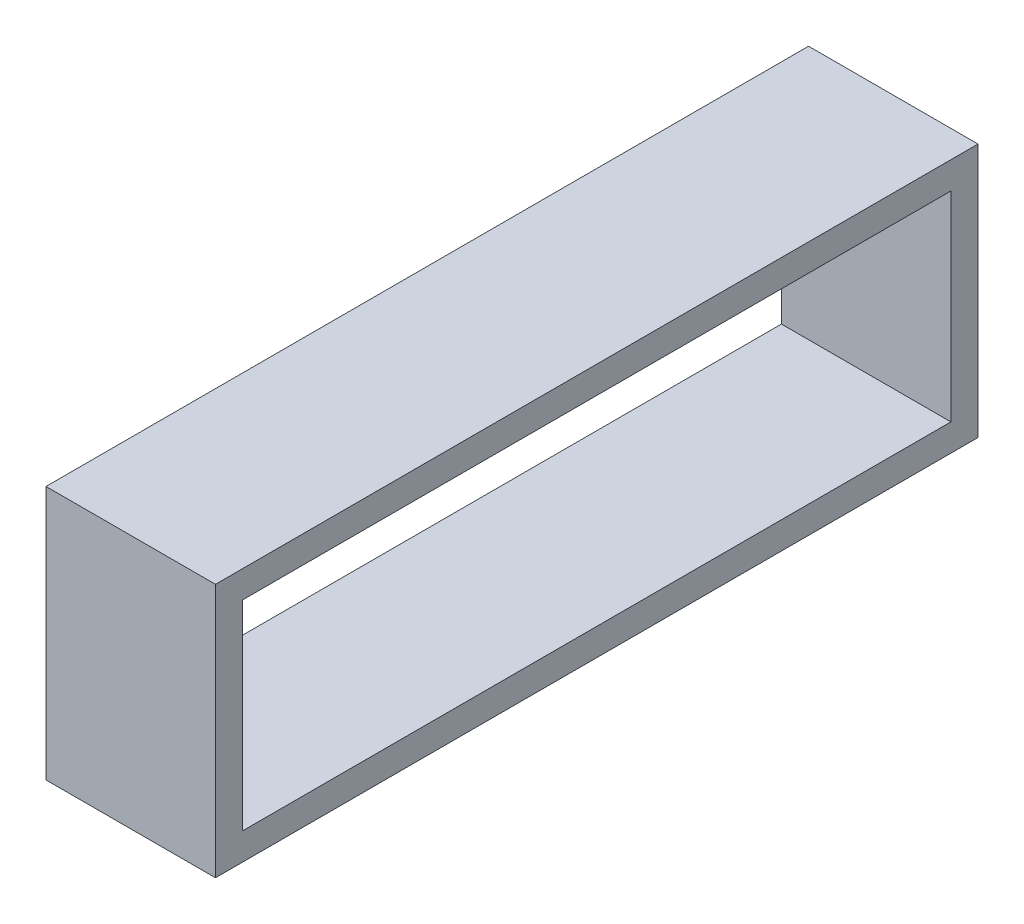
SolidWorks part; units mm, degrees
ref_plane "Front Plane" through (0, 0, 0) normal (0, 0, 1) x (1, 0, 0)
ref_plane "Top Plane" through (0, 0, 0) normal (0, 1, 0) x (1, 0, 0)
ref_plane "Right Plane" through (0, 0, 0) normal (1, 0, 0) x (0, 0, -1)
sketch "Sketch1" plane through (0, 0, 0) normal (0, 0, 1) x (1, 0, 0)
  line L0 (0, -34.589) -> (0, 55.433) construction
  line L5 (6.35, 0) -> (-6.35, 0)
  line L6 (0, 0) -> (0, -19.05)
  line L7 (6.35, -19.05) -> (-6.35, -19.05)
  line L8 (-6.35, 0) -> (-6.35, -19.05)
  line L9 (-6.35, 0) -> (-43.5006, 0)
  line L13 (6.35, 0) -> (6.35, -19.05)
  line L16 (6.35, 0) -> (43.5006, 0)
  dimension "D1" = 6.35
  dimension "D2" = 19.05
extrude "Boss-Extrude1" add sketch "Sketch1" along normal blind 57.15
sketch "Sketch3" plane through (-6.35, 0, 0) normal (-1, 0, 0) x (0, 0, 1)
  line L0 (57.15, -19.05) -> (0, -19.05) construction
  line L1 (2.032, -2.032) -> (55.118, -2.032)
  line L2 (2.032, -2.032) -> (2.032, -17.018)
  line L3 (2.032, -17.018) -> (55.118, -17.018)
  line L4 (55.118, -2.032) -> (55.118, -17.018)
  line L6 (57.15, 0) -> (0, 0) construction
  line L7 (57.15, 0) -> (57.15, -19.05) construction
  line L8 (0, 0) -> (0, -19.05) construction
  dimension "D1" = 2.032
  dimension "D2" = 2.032
  dimension "D3" = 2.032
  dimension "D4" = 2.032
extrude "Cut-Extrude2" cut sketch "Sketch3" against normal blind 124.46
